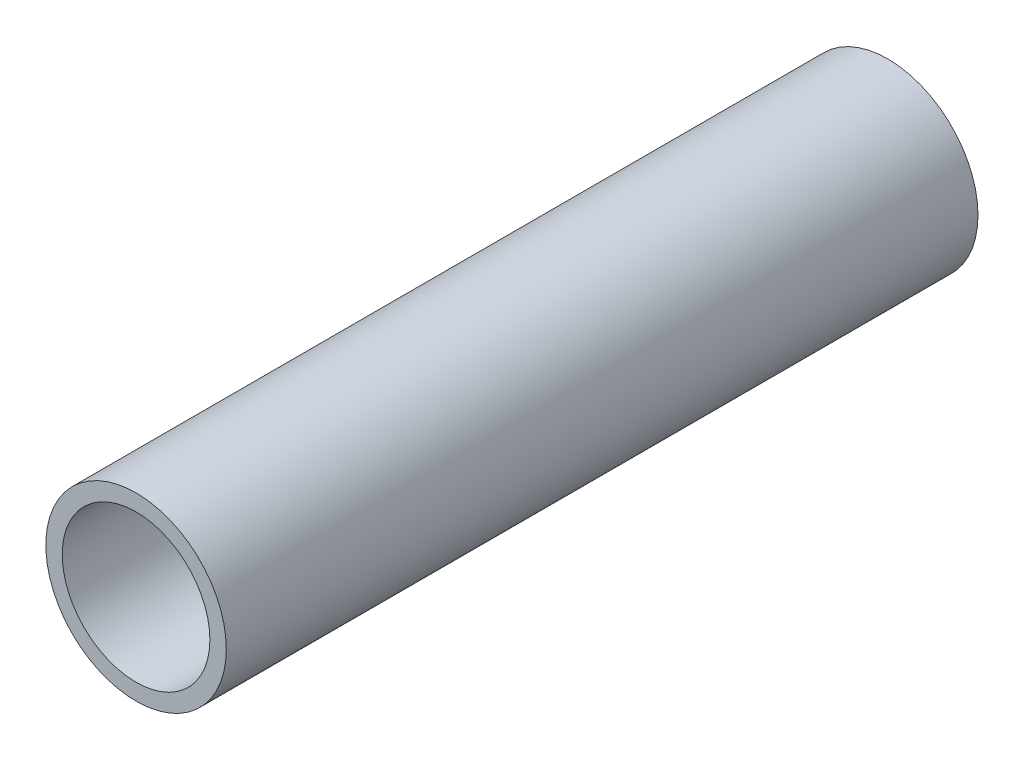
SolidWorks part; units mm, degrees
ref_plane "Front Plane" through (0, 0, 0) normal (0, 0, 1) x (1, 0, 0)
ref_plane "Top Plane" through (0, 0, 0) normal (0, 1, 0) x (1, 0, 0)
ref_plane "Right Plane" through (0, 0, 0) normal (1, 0, 0) x (0, 0, -1)
sketch "Sketch1" plane through (0, 0, 0) normal (0, 0, 1) x (1, 0, 0)
  circle A0 centre (0, 0) radius 5.335
  circle A1 centre (0, 0) radius 4.365
  dimension "D1" = 10.67
  dimension "D2" = 0.97
extrude "Boss-Extrude1" add sketch "Sketch1" along normal blind 44.45
